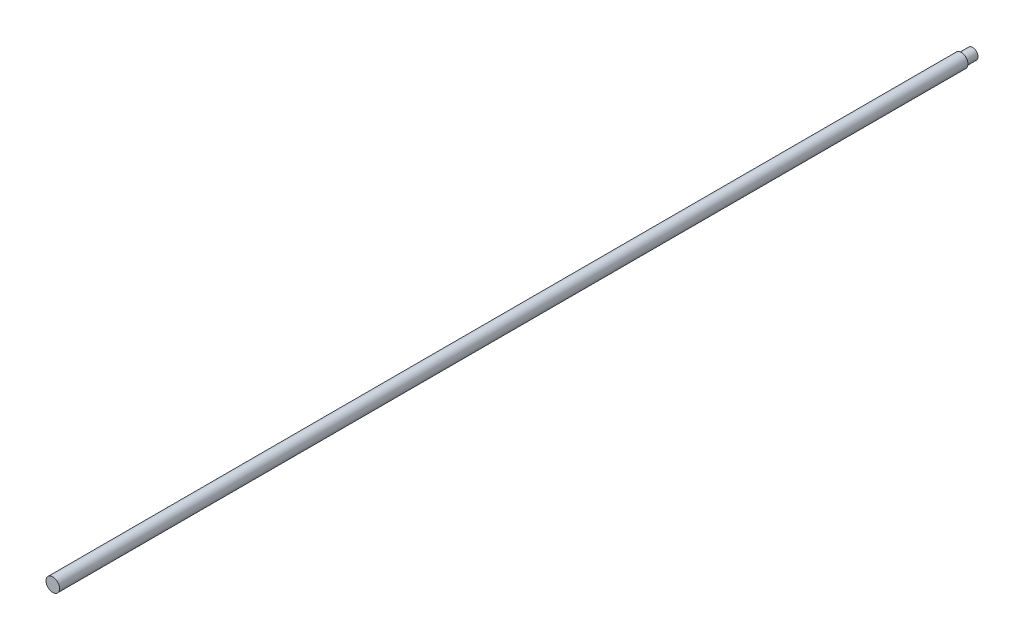
SolidWorks part; units mm, degrees
material "AISI 1020"
ref_plane "Plan de face" through (0, 0, 0) normal (0, 0, 1) x (1, 0, 0)
ref_plane "Plan de dessus" through (0, 0, 0) normal (0, 1, 0) x (1, 0, 0)
ref_plane "Plan de droite" through (0, 0, 0) normal (1, 0, 0) x (0, 0, -1)
sketch "Esquisse1" plane through (0, 0, 0) normal (0, 0, 1) x (1, 0, 0)
  circle A0 centre (0, 0) radius 2.5
  dimension "D1" = 5
extrude "Boss.-Extru.1" add sketch "Esquisse1" along normal blind 340
sketch "Esquisse2" plane through (0, 0, 0) normal (0, 0, -1) x (-1, 0, 0)
  circle A0 centre (0, 0) radius 2
  dimension "D1" = 4
extrude "Enlèv. mat.-Extru.1" cut sketch "Esquisse2" against normal blind 4.2 flip side to cut
hole_wizard "Trou taraudé M3x0.51" positions "Esquisse3" profile "Esquisse4" tap size "M3x0.5" standard "Ansi Metric"
sketch "Esquisse3" plane through (0, 0, 0) normal (0, 0, -1) x (-1, 0, 0)
  point P0 (0, 0)
sketch "Esquisse4" plane through (0, 0, 0) normal (1, 0, 0) x (0, 1, 0)
  line L0 (0, 0) -> (0, 9.2511)
  line L1 (0, 9.2511) -> (1.25, 8.5)
  line L2 (1.25, 8.5) -> (1.25, 0)
  line L5 (1.25, 0) -> (0, 0)
  line L10 (0, 9.2511) -> (-1.25, 8.5) construction
  line L11 (0, -6.35) -> (0, 107.95) construction
  dimension "Diamètre du trou pour taraudage" = 2.5
  dimension "Profondeur du trou pour taraudage" = 8.5
  dimension "Angle de pointe" = 118
cosmetic thread "Filetage de perçage1" parameters "D1"=6, "D2"=3
